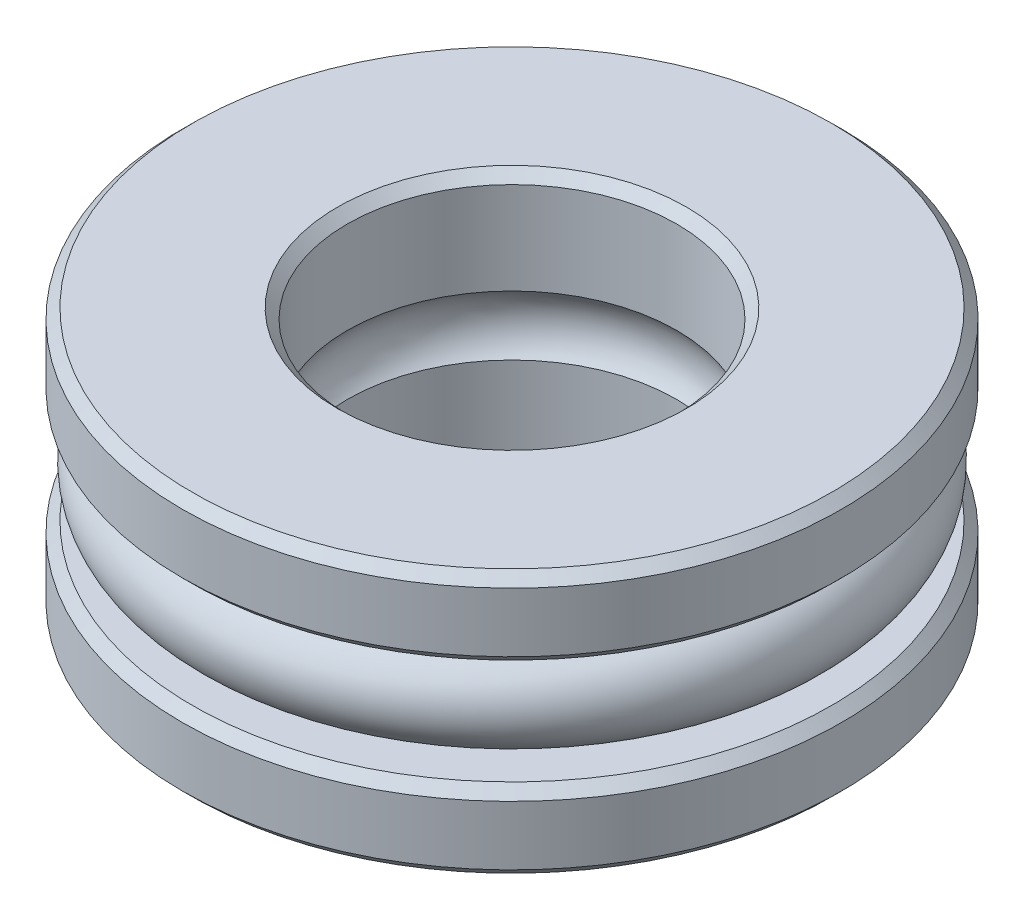
SolidWorks part; units mm, degrees
ref_plane "Front Plane" through (0, 0, 0) normal (0, 0, 1) x (1, 0, 0)
ref_plane "Top Plane" through (0, 0, 0) normal (0, 1, 0) x (1, 0, 0)
ref_plane "Right Plane" through (0, 0, 0) normal (1, 0, 0) x (0, 0, -1)
sketch "Sketch1" plane through (0, 0, 0) normal (0, 0, 1) x (1, 0, 0)
  line L0 (0, -7.5752) -> (0, 14.8699) construction
  line L2 (5, 1.8517) -> (5, 0.95)
  line L8 (2.5, -1.85) -> (2.5, 1.8517)
  line L9 (4, 0) -> (-4, 0) construction
  line L10 (2.5, 1.8517) -> (2.6483, 2)
  line L11 (2.6483, 2) -> (4.85, 2)
  line L12 (4.85, 2) -> (5, 1.8517)
  line L13 (5, -1.85) -> (4.85, -2)
  line L14 (4.85, -2) -> (2.6483, -2)
  line L15 (2.6483, -2) -> (2.5, -1.85)
  line L16 (4.2, 0.8) -> (4.85, 0.8)
  line L17 (4.2, 0.8) -> (4.2, -0.8)
  line L18 (4.2, -0.8) -> (4.85, -0.8)
  line L19 (4.85, -0.8) -> (5, -0.95)
  line L20 (4.85, 0.8) -> (5, 0.95)
  line L21 (5, -0.95) -> (5, -1.85)
  circle A0 centre (4.2, 0) radius 0.675
  circle A1 centre (2, 0) radius 0.675
  dimension "D8" = 0.1483
  dimension "D16" = 1.35
  dimension "D21" = 1.35
  dimension "D1" = 2.5
  dimension "D2" = 0.15
  dimension "D3" = 4
  dimension "D4" = 5
  dimension "D5" = 0.1483
  dimension "D6" = 0.1483
  dimension "D7" = 0.15
  dimension "D9" = 0.15
  dimension "D10" = 0.15
  dimension "D11" = 0.15
  dimension "D12" = 0.1483
  dimension "D13" = 0.15
  dimension "D14" = 0.15
  dimension "D15" = 0.15
  dimension "D17" = 1.6
  dimension "D18" = 0
  dimension "D19" = 4.2
  dimension "D20" = 2
  dimension "D22" = 2
revolve "Revolve1" add sketch "Sketch1" angle 360 about L0
